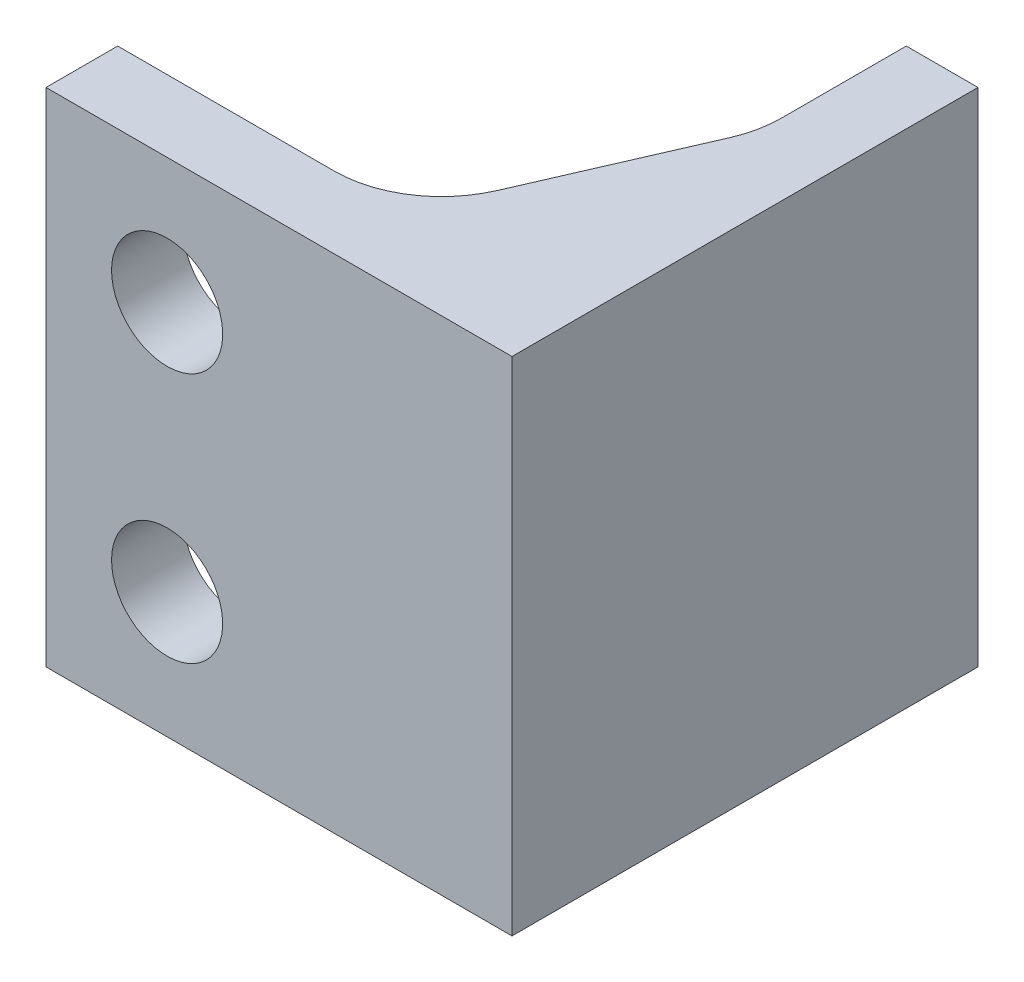
SolidWorks part; units mm, degrees
ref_plane "Спереди" through (0, 0, 0) normal (0, 0, 1) x (1, 0, 0)
ref_plane "Сверху" through (0, 0, 0) normal (0, 1, 0) x (1, 0, 0)
ref_plane "Справа" through (0, 0, 0) normal (1, 0, 0) x (0, 0, -1)
other "Configuration Table"
sketch "Sketch1" plane through (0, 0, 0) normal (0, 1, 0) x (1, 0, 0)
  line L0 (0, 0) -> (-13, 0)
  line L1 (-13, 0) -> (-13, 2)
  line L2 (-13, 2) -> (-6.9668, 2)
  line L3 (-2, 9.5226) -> (-2, 13)
  line L4 (-2, 13) -> (0, 13)
  line L5 (0, 13) -> (0, 0)
  line L7 (-4.2157, 3.8036) -> (-2.2489, 8.3262)
  arc A2 (-2, 9.5226) -> (-2.2489, 8.3262) centre (-5, 9.5226) cw
  arc A3 (-4.2157, 3.8036) -> (-6.9668, 2) centre (-6.9668, 5) cw
  point P10 (-5, 2)
  point P13 (-5, 2)
  dimension "D3" = 2
  dimension "D5" = 3
  dimension "D1" = 13
  dimension "D2" = 11
  dimension "D4" = 8
extrude "Boss-Extrude1" add sketch "Sketch1" along normal blind 7
sketch "Sketch3" plane through (0, 0, -2) normal (0, 0, -1) x (-1, 0, 0)
  line L0 (13, 7) -> (13, 0) construction
  circle A0 centre (9.6213, 3.5) radius 1.55
  dimension "D2" = 3.1
  dimension "D1" = 3.3787
extrude "Cut-Extrude1" cut sketch "Sketch3" against normal up to next
mirror "Mirror1" about plane through (-6.9668, 7, -5) normal (0, -1, 0) of bodies 104 105
